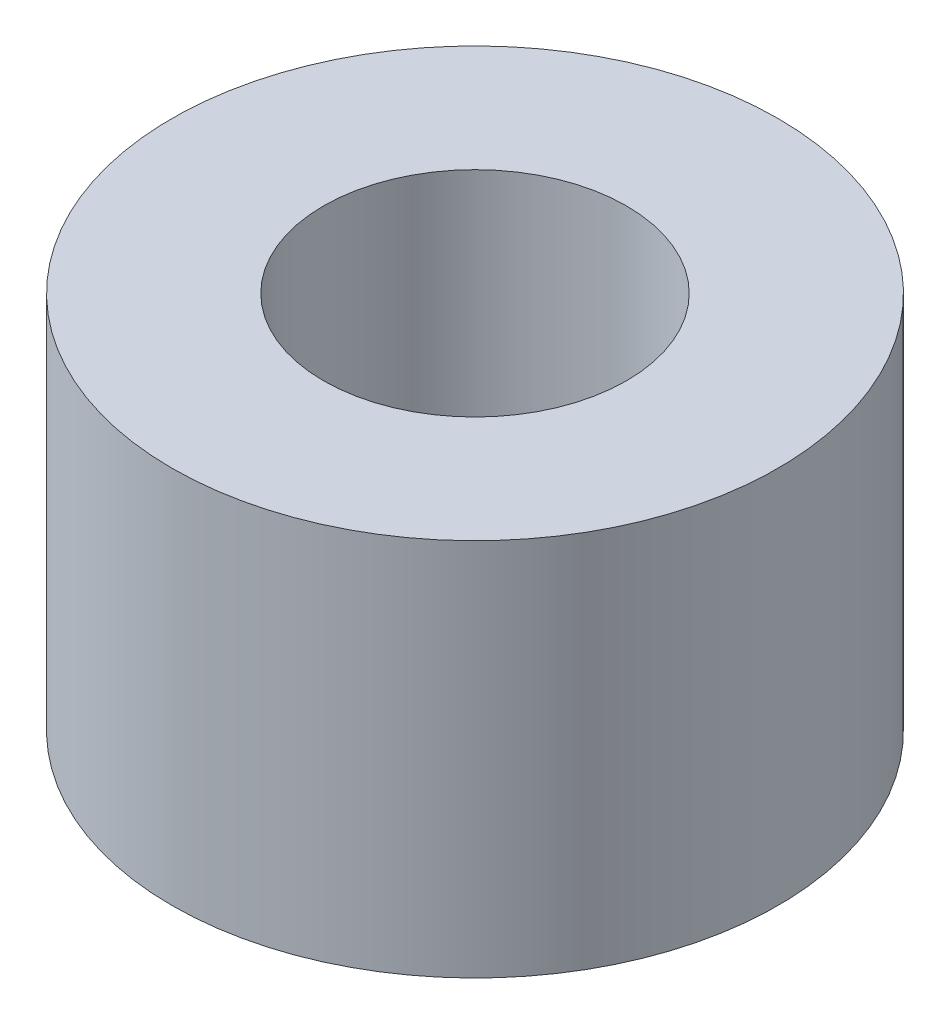
SolidWorks part; units mm, degrees
ref_plane "前视基准面" through (0, 0, 0) normal (0, 0, 1) x (1, 0, 0)
ref_plane "上视基准面" through (0, 0, 0) normal (0, 1, 0) x (1, 0, 0)
ref_plane "右视基准面" through (0, 0, 0) normal (1, 0, 0) x (0, 0, -1)
sketch "草图1" plane through (0, 0, 0) normal (0, 1, 0) x (1, 0, 0)
  circle A0 centre (0, 0) radius 1
  circle A1 centre (0, 0) radius 2
  dimension "D1" = 2
  dimension "D2" = 4
extrude "凸台-拉伸1" add sketch "草图1" along normal blind 2.5
